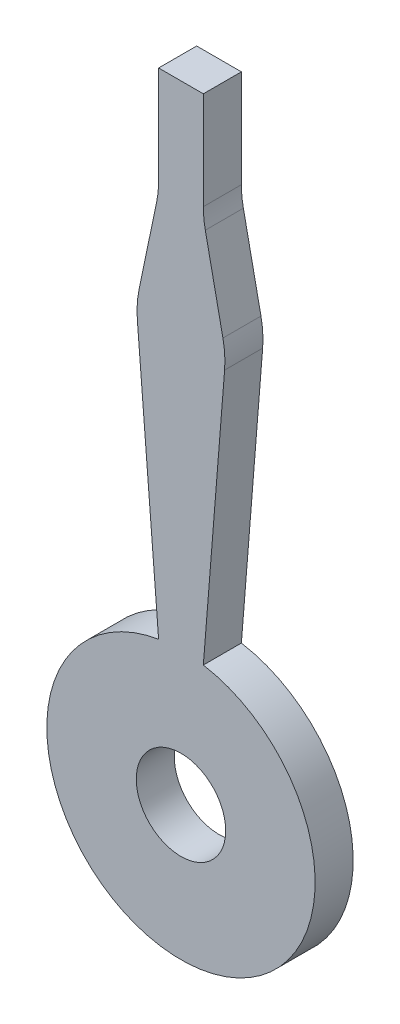
SolidWorks part; units mm, degrees
ref_plane "Front Plane" through (0, 0, 0) normal (0, 0, 1) x (1, 0, 0)
ref_plane "Top Plane" through (0, 0, 0) normal (0, 1, 0) x (1, 0, 0)
ref_plane "Right Plane" through (0, 0, 0) normal (1, 0, 0) x (0, 0, -1)
sketch "Sketch1" plane through (0, 0, 0) normal (0, 0, 1) x (1, 0, 0)
  line L0 (0, 0) -> (4.7, 0)
  line L1 (0, -14.1) -> (0, 65.9)
  line L2 (-4.7, 13.2936) -> (-4.7, 43.2936)
  line L3 (4.7, 13.2936) -> (4.7, 43.2936)
  line L4 (-4.4082, 44.6972) -> (-2.5594, 53.5898)
  line L5 (-2.35, 55.6253) -> (-2.35, 65.9)
  line L6 (-2.35, 65.9) -> (2.35, 65.9)
  line L7 (2.35, 65.9) -> (2.35, 55.6253)
  line L8 (2.5594, 53.5898) -> (4.4082, 44.6972)
  line L9 (-2.35, 13.9028) -> (-4.5857, 41.8646)
  line L10 (2.35, 13.9028) -> (4.5857, 41.8646)
  circle A0 centre (0, 0) radius 4.7
  circle A1 centre (0, 0) radius 14.1
  arc A2 (4.4082, 44.6972) -> (4.5857, 41.8646) centre (-5.3824, 42.6616) cw
  arc A3 (-4.4082, 44.6972) -> (-4.5857, 41.8646) centre (5.3824, 42.6616) ccw
  arc A4 (-2.35, 55.6253) -> (-2.5594, 53.5898) centre (-12.35, 55.6253) cw
  arc A5 (2.35, 55.6253) -> (2.5594, 53.5898) centre (12.35, 55.6253) ccw
  point P7 (-4.7, 0)
  point P8 (14.1, 0)
  point P9 (-14.1, 0)
  point P10 (4.7, 13.2936)
  point P11 (-4.7, 13.2936)
  point P16 (2.35, 54.5968)
  point P17 (-2.35, 54.5968)
  point P22 (-2.35, 13.9028)
  point P23 (2.35, 13.9028)
  point P34 (-2.35, 54.5968)
  point P37 (2.35, 54.5968)
  dimension "D3" = 28.2
  dimension "D8" = 10
  dimension "D9" = 10
  dimension "D10" = 10
  dimension "D11" = 10
  dimension "D1" = 4.7
  dimension "D2" = 80
  dimension "D4" = 30
  dimension "D5" = 30
  dimension "D6" = 13.2936
  dimension "D7" = 13.2936
  dimension "D12" = 4.7
  dimension "D13" = 27.9618
  dimension "D14" = 27.9618
  dimension "D15" = 10.2747
  dimension "D16" = 10.2747
  dimension "D17" = 23.49
extrude "Boss-Extrude1" add sketch "Sketch1" along normal blind 4 contours A1 L1 A0 | L1 A1 A0 | L5 A4 L4 A3 L9 A1 L1 L6 | A5 L7 L6 L1 A1 L10 A2 L8
